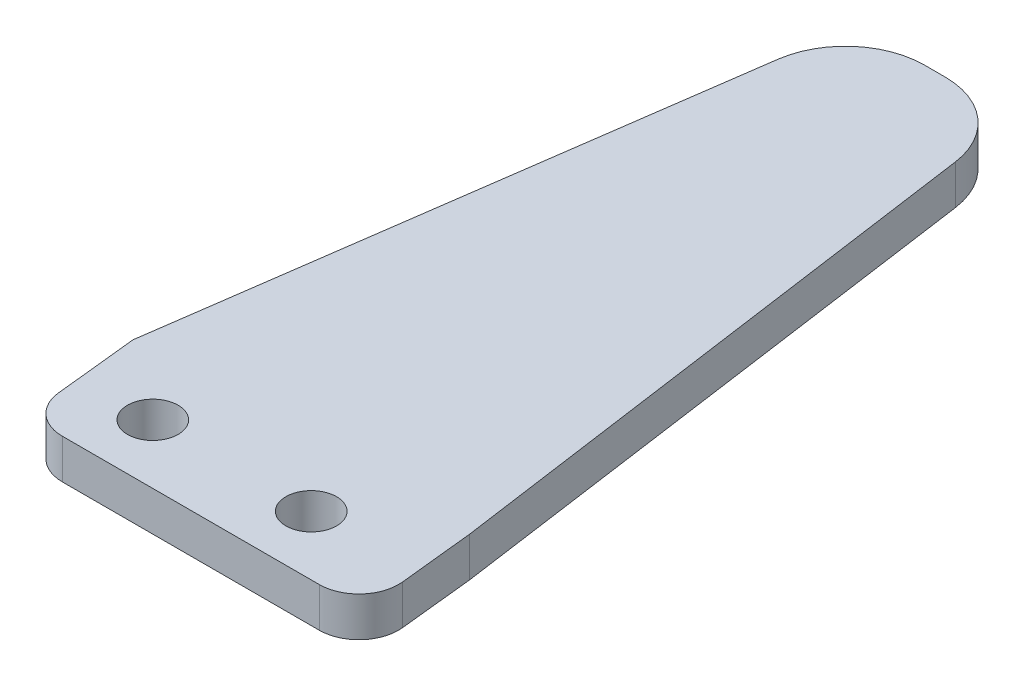
SolidWorks part; units mm, degrees
ref_plane "Front Plane" through (0, 0, 0) normal (0, 0, 1) x (1, 0, 0)
ref_plane "Top Plane" through (0, 0, 0) normal (0, 1, 0) x (1, 0, 0)
ref_plane "Right Plane" through (0, 0, 0) normal (1, 0, 0) x (0, 0, -1)
sketch "Sketch1" plane through (0, 0, 0) normal (0, 1, 0) x (1, 0, 0)
  line L0 (44.45, 9.525) -> (45.4511, 0)
  line L14 (44.45, 9.525) -> (51.5938, 60.325)
  line L15 (72.4386, 0) -> (71.4375, 9.525)
  line L16 (71.4375, 9.525) -> (64.2938, 60.325)
  line L17 (64.2938, 60.325) -> (51.5938, 60.325)
  line L18 (45.4511, 0) -> (72.4386, 0)
  circle A0 centre (50.8, 4.7625) radius 2.032
  circle A1 centre (63.5, 4.7625) radius 2.032
  circle A3 centre (63.5, 4.7625) radius 1.905 construction
  point P0 (50.8, 60.325)
  dimension "D2" = 4.064
  dimension "D1" = 50.8
  dimension "D3" = 84
  dimension "D4" = 50.8
  dimension "D5" = 9.525
  dimension "D6" = 4.7625
  dimension "D7" = 26.9875
  dimension "D8" = 7.9375
  dimension "D9" = 12.7
extrude "Boss-Extrude1" add sketch "Sketch1" along normal blind 3.175
fillet "Fillet1" radius 6.35 2 edges at (51.5938, 1.5875, -60.325) (64.2938, 1.5875, -60.325)
fillet "Fillet2" radius 3.175 2 edges at (72.4386, 1.5875, 0) (45.4511, 1.5875, 0)
